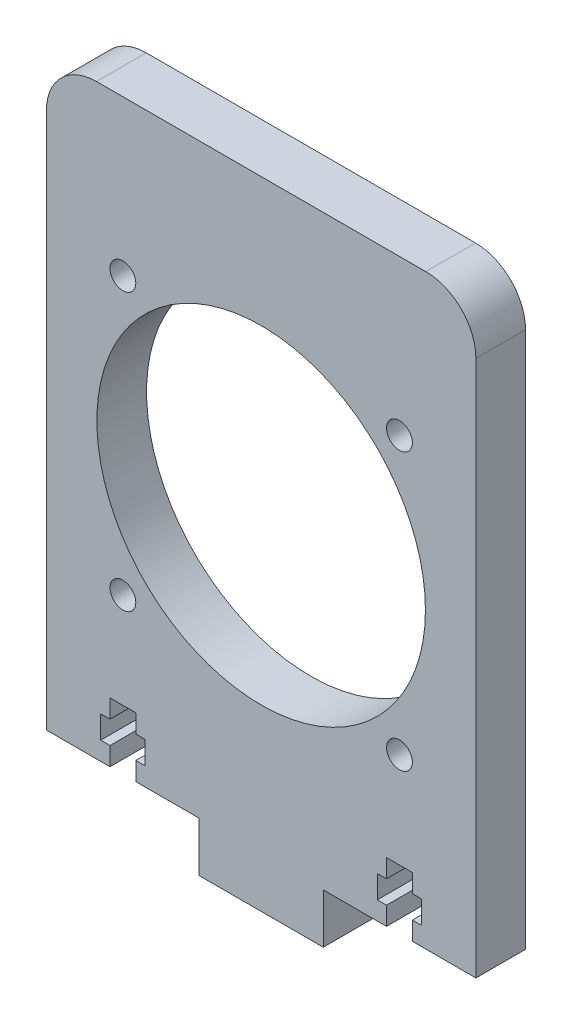
SolidWorks part; units mm, degrees
ref_plane "Front Plane" through (0, 0, 0) normal (0, 0, 1) x (1, 0, 0)
ref_plane "Top Plane" through (0, 0, 0) normal (0, 1, 0) x (1, 0, 0)
ref_plane "Right Plane" through (0, 0, 0) normal (1, 0, 0) x (0, 0, -1)
sketch "Sketch1" plane through (0, 0, 0) normal (0, 0, 1) x (1, 0, 0)
  line L0 (0, 0) -> (-35.3553, 35.3553) construction
  line L1 (-54.9, 75) -> (54.9, 75)
  line L2 (-54.9, 75) -> (-54.9, -75)
  line L3 (-54.9, -75) -> (54.9, -75)
  line L4 (54.9, 75) -> (54.9, -75)
  line L7 (-54.9, 0) -> (54.9, 0) construction
  line L8 (0, 75) -> (0, -75) construction
  circle A0 centre (0, 0) radius 42
  circle A1 centre (-35.3553, 35.3553) radius 3.3
  circle A2 centre (35.3553, 35.3553) radius 3.3
  circle A3 centre (35.3553, -35.3553) radius 3.3
  circle A4 centre (-35.3553, -35.3553) radius 3.3
  dimension "D1" = 84
  dimension "D5" = 6.6
  dimension "D2" = 109.8
  dimension "D3" = 150
  dimension "D4" = 45
  dimension "D6" = 50
extrude "Boss-Extrude1" add sketch "Sketch1" along normal blind 12.7
sketch "Sketch2" plane through (0, 0, 0) normal (0, 0, -1) x (-1, 0, 0)
  line L0 (0, -75) -> (32.05, -75)
  line L1 (54.9, -75) -> (-54.9, -75) construction
  line L2 (32.05, -75) -> (32.05, -70.3)
  line L3 (32.05, -70.3) -> (29.686, -70.3)
  line L4 (29.686, -70.3) -> (29.686, -64.46)
  line L5 (29.686, -64.46) -> (32.05, -64.46)
  line L6 (32.05, -64.46) -> (32.05, -59.76)
  line L7 (32.05, -59.76) -> (38.65, -59.76)
  line L8 (38.65, -59.76) -> (38.65, -64.46)
  line L9 (38.65, -64.46) -> (41.014, -64.46)
  line L10 (41.014, -64.46) -> (41.014, -70.3)
  line L11 (41.014, -70.3) -> (38.65, -70.3)
  line L12 (38.65, -70.3) -> (38.65, -75)
  line L13 (38.65, -75) -> (32.05, -75)
  line L14 (0, -75) -> (0, 0) construction
  line L15 (-38.65, -75) -> (-32.05, -75)
  line L16 (-38.65, -70.3) -> (-38.65, -75)
  line L17 (-41.014, -70.3) -> (-38.65, -70.3)
  line L18 (-41.014, -64.46) -> (-41.014, -70.3)
  line L19 (-38.65, -64.46) -> (-41.014, -64.46)
  line L20 (-38.65, -59.76) -> (-38.65, -64.46)
  line L21 (-32.05, -59.76) -> (-38.65, -59.76)
  line L22 (-32.05, -64.46) -> (-32.05, -59.76)
  line L23 (-29.686, -64.46) -> (-32.05, -64.46)
  line L24 (-29.686, -70.3) -> (-29.686, -64.46)
  line L25 (-32.05, -70.3) -> (-29.686, -70.3)
  line L26 (-32.05, -75) -> (-32.05, -70.3)
  line M18 (-54.9, -75) -> (54.9, -75)
  dimension "D1" = 32.05
  dimension "D2" = 5.84
  dimension "D3" = 6.6
  dimension "D4" = 15.24
  dimension "D5" = 11.328
extrude "Cut-Extrude1" cut sketch "Sketch2" against normal through all contours L26 L25 L24 L23 L22 L21 L20 L19 L18 L17 L16 M18 | L2 L3 L4 L5 L6 L7 L8 L9 L10 L11 L12 L13
sketch "Sketch4" plane through (0, -75, 0) normal (0, -1, 0) x (1, 0, 0)
  line L0 (0, 0) -> (15.875, 0)
  line L1 (-32.05, 0) -> (32.05, 0) construction
  line L2 (15.875, 0) -> (15.875, 12.7)
  line L3 (-32.05, 12.7) -> (32.05, 12.7) construction
  line L4 (15.875, 12.7) -> (-15.875, 12.7)
  line L5 (-15.875, 12.7) -> (-15.875, 0)
  line L6 (-15.875, 0) -> (0, 0)
  dimension "D1" = 31.75
extrude "Boss-Extrude2" add sketch "Sketch4" along normal blind 12.7
fillet "Fillet1" radius 12.8 2 edges at (-54.9, 75, 6.35) (54.9, 75, 6.35)
